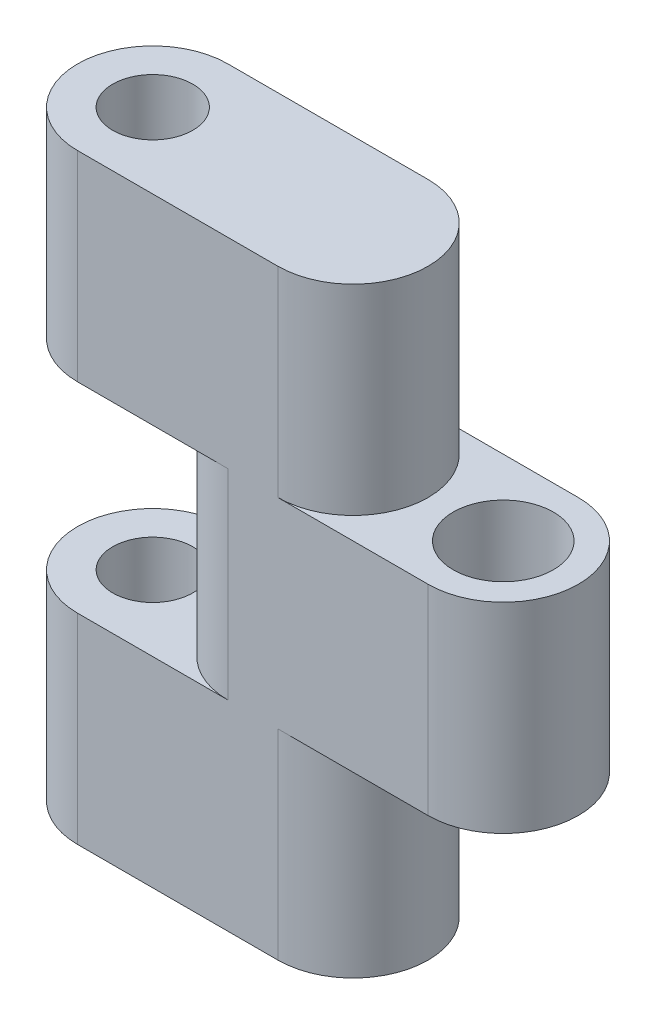
SolidWorks part; units mm, degrees
ref_plane "前视基准面" through (0, 0, 0) normal (0, 0, 1) x (1, 0, 0)
ref_plane "上视基准面" through (0, 0, 0) normal (0, 1, 0) x (1, 0, 0)
ref_plane "右视基准面" through (0, 0, 0) normal (1, 0, 0) x (0, 0, -1)
sketch "草图2" plane through (0, 0, 0) normal (0, 1, 0) x (1, 0, 0)
  line L1 (0, 0) -> (7, 0)
  line L2 (0, 0) -> (0, -3) construction
  line L3 (0, -3) -> (7, -3)
  line L4 (7, 0) -> (7, -3) construction
  arc A0 (0, 0) -> (0, -3) centre (0, -1.5) ccw
  arc A1 (7, -3) -> (7, 0) centre (7, -1.5) ccw
  circle A2 centre (0, -1.5) radius 0.8
  circle A3 centre (7, -1.5) radius 1
  dimension "D1" = 1.6
  dimension "D2" = 2
  dimension "D3" = 7
  dimension "D4" = 3
extrude "凸台-拉伸1" add sketch "草图2" along normal blind 12
sketch "草图4" plane through (0, 0, 0) normal (0, -1, 0) x (1, 0, 0)
  line L0 (4, 0) -> (4, 3) construction
  line L1 (7, 0) -> (0, 0) construction
  line L2 (0, 3) -> (7, 3) construction
  line L4 (7, 0) -> (4, 0)
  line L5 (7, 3) -> (4, 3)
  arc A0 (4, 0) -> (4, 3) centre (4, 1.5) ccw
  arc A1 (7, 0) -> (7, 3) centre (7, 1.5) ccw construction
  arc A2 (7, 0) -> (7, 3) centre (7, 1.5) ccw
  dimension "D1" = 3
extrude "切除-拉伸1" cut sketch "草图4" against normal blind 4
ref_plane "基准面1" through (0, 6, 0) normal (0, -1, 0) x (-1, 0, 0)
mirror "镜向1" about plane through (0, 6, 0) normal (0, -1, 0) of "切除-拉伸1"
sketch "草图5" plane through (0, 6, 0) normal (0, -1, 0) x (1, 0, 0)
  line L0 (0, 3) -> (3, 3)
  line L1 (3, 0) -> (3, 3) construction
  line L2 (4, 0) -> (0, 0) construction
  line L3 (0, 3) -> (4, 3) construction
  line L4 (0, 0) -> (3, 0)
  arc A0 (3, 3) -> (3, 0) centre (3, 1.5) ccw
  circle A1 centre (0, 1.5) radius 0.8 construction
  arc A2 (0, 3) -> (0, 0) centre (0, 1.5) ccw construction
  arc A3 (0, 3) -> (0, 0) centre (0, 1.5) ccw
  dimension "D1" = 3
extrude "切除-拉伸2" cut sketch "草图5" against normal blind 2 and the other way blind 2
